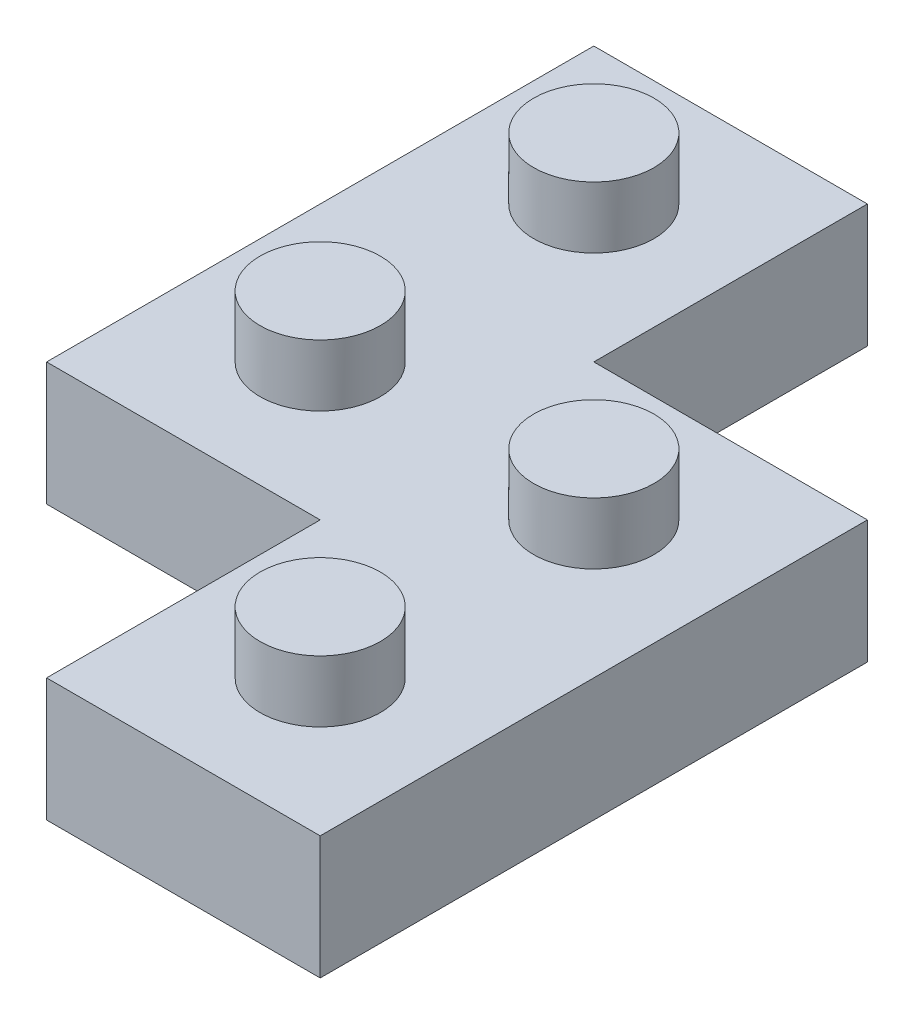
SolidWorks part; units mm, degrees
material "ABS"
ref_plane "Front Plane" through (0, 0, 0) normal (0, 0, 1) x (1, 0, 0)
ref_plane "Top Plane" through (0, 0, 0) normal (0, 1, 0) x (1, 0, 0)
ref_plane "Right Plane" through (0, 0, 0) normal (1, 0, 0) x (0, 0, -1)
sketch "Sketch1" plane through (0, 0, 0) normal (0, 1, 0) x (1, 0, 0)
  line L0 (-5.6746, 20.3112) -> (7.0254, 20.3112)
  line L1 (7.0254, 20.3112) -> (7.0254, 7.6112)
  line L2 (7.0254, 7.6112) -> (19.7254, 7.6112)
  line L3 (19.7254, 7.6112) -> (19.7254, -17.7888)
  line L4 (19.7254, -17.7888) -> (7.0254, -17.7888)
  line L5 (7.0254, -17.7888) -> (7.0254, -5.0888)
  line L6 (7.0254, -5.0888) -> (-5.6746, -5.0888)
  line L7 (-5.6746, -5.0888) -> (-5.6746, 20.3112)
  dimension "D1" = 38.1
  dimension "D2" = 12.7
  dimension "D3" = 12.7
  dimension "D4" = 12.7
  dimension "D5" = 12.7
extrude "Boss-Extrude1" add sketch "Sketch1" along normal blind 5.715
sketch "Sketch2" plane through (0, 5.715, 0) normal (0, 1, 0) x (1, 0, 0)
  line L0 (-5.6746, 20.3112) -> (-5.6746, -5.0888) construction
  line L1 (19.7254, -17.7888) -> (19.7254, 7.6112) construction
  line L2 (7.0254, 20.3112) -> (-5.6746, 20.3112) construction
  circle A0 centre (0.6754, 1.2612) radius 2.794
  circle A1 centre (13.3754, 1.2612) radius 2.794
  circle A2 centre (0.6754, 13.9612) radius 2.794
  circle A3 centre (13.3754, -11.4388) radius 2.794
  dimension "D2" = 6.35
  dimension "D4" = 6.35
  dimension "D5" = 12.7
  dimension "D3" = 6.35
  dimension "D6" = 12.7
  dimension "D1" = 2
extrude "Boss-Extrude3" add sketch "Sketch2" along normal blind 2.8575
